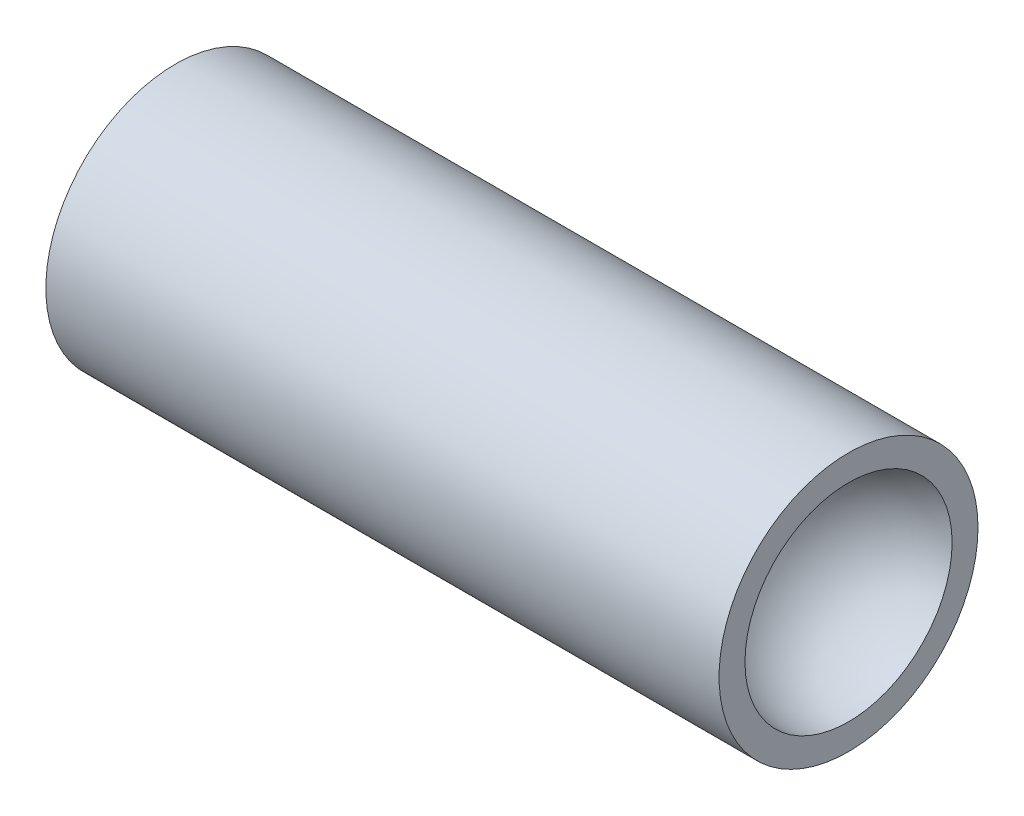
SolidWorks part; units mm, degrees
ref_plane "Front Plane" through (0, 0, 0) normal (0, 0, 1) x (1, 0, 0)
ref_plane "Top Plane" through (0, 0, 0) normal (0, 1, 0) x (1, 0, 0)
ref_plane "Right Plane" through (0, 0, 0) normal (1, 0, 0) x (0, 0, -1)
sketch "Sketch1" plane through (0, 0, 0) normal (1, 0, 0) x (0, 0, -1)
  circle A0 centre (0, 0) radius 25
  dimension "D1" = 50
extrude "Boss-Extrude1" add sketch "Sketch1" along normal blind 130
ref_plane "Plane1" through (131.016, 0, 0) normal (1, 0, 0) x (0, 0, -1)
sketch "Sketch2" plane through (130, 0, 0) normal (1, 0, 0) x (0, 0, -1)
  line L0 (-20, 0) -> (20, 0)
  arc A2 (-20, 0) -> (20, 0) centre (0, 0) cw
  dimension "D1" = 20
revolve "Cut-Revolve3" cut sketch "Sketch2" angle 360 about L0
sketch "Sketch3" plane through (0, 0, 0) normal (-1, 0, 0) x (0, 0, 1)
  circle A0 centre (0, 0) radius 20
  dimension "D1" = 40
extrude "Cut-Extrude1" cut sketch "Sketch3" against normal blind 100
ref_plane "Plane2" through (160, 0, 0) normal (1, 0, 0) x (0, 0, -1)
sketch "Sketch4" plane through (160, 0, 0) normal (1, 0, 0) x (0, 0, -1)
  circle A0 centre (0, 0) radius 25 construction
  circle A1 centre (0, 0) radius 25
